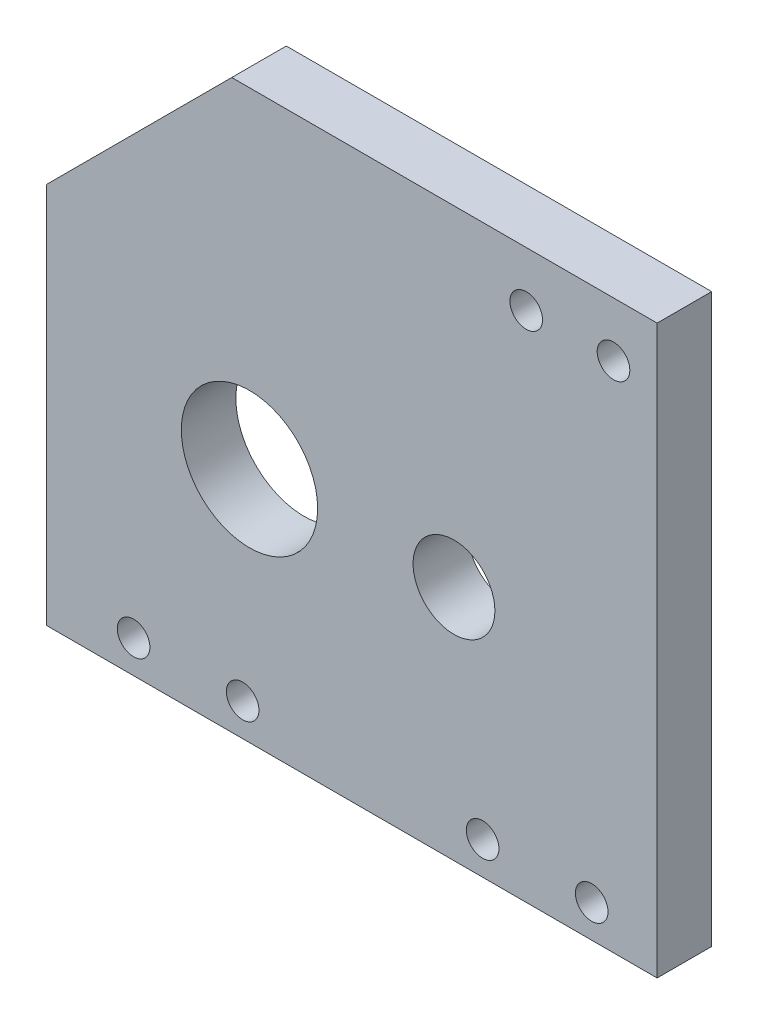
SolidWorks part; units mm, degrees
ref_plane "Front Plane" through (0, 0, 0) normal (0, 0, 1) x (1, 0, 0)
ref_plane "Top Plane" through (0, 0, 0) normal (0, 1, 0) x (1, 0, 0)
ref_plane "Right Plane" through (0, 0, 0) normal (1, 0, 0) x (0, 0, -1)
sketch "Sketch1" plane through (0, 0, 0) normal (0, 0, 1) x (1, 0, 0)
  line L1 (35.56, -33.02) -> (-35.56, -33.02)
  line L2 (35.56, -33.02) -> (35.56, 33.02)
  line L3 (35.56, 33.02) -> (-35.56, 33.02)
  line L4 (-35.56, -33.02) -> (-35.56, 33.02)
  line L5 (35.56, -33.02) -> (-35.56, 33.02) construction
  line L6 (35.56, 33.02) -> (-35.56, -33.02) construction
  circle A2 centre (-11.9062, -5.4381) radius 7.9375
  circle A3 centre (11.9062, -5.4381) radius 4.7625
  point P0 (0, 0)
  dimension "D11" = 15.875
  dimension "D12" = 9.525
  dimension "D1" = 71.12
  dimension "D2" = 66.04
  dimension "D9" = 5.4381
  dimension "D10" = 5.4381
  dimension "D13" = 11.9062
  dimension "D14" = 11.9062
extrude "Boss-Extrude1" add sketch "Sketch1" along normal blind 6.35
hole_wizard "#6 Clearance Hole1" positions "Sketch2" profile "Sketch3" hole size "#6" standard "ANSI Inch" end condition through all
sketch "Sketch2" plane through (0, 0, 6.35) normal (0, 0, 1) x (1, 0, 0)
  line L0 (-25.4, -29.21) -> (-12.7, -29.21)
  line L2 (15.24, -29.21) -> (27.94, -29.21)
  line L4 (-35.56, -33.02) -> (35.56, -33.02) construction
  line L5 (-35.56, 33.02) -> (-35.56, -33.02) construction
  point P0 (-25.4, -29.21)
  point P2 (-12.7, -29.21)
  point P4 (15.24, -29.21)
  point P6 (27.94, -29.21)
  dimension "D1" = 12.7
  dimension "D2" = 12.7
  dimension "D3" = 3.81
  dimension "D4" = 3.81
  dimension "D5" = 10.16
  dimension "D6" = 27.94
sketch "Sketch3" plane through (-25.4, -29.21, 6.35) normal (1, 0, 0) x (0, -1, 0)
  line L0 (0, 0) -> (0, 6.35)
  line L1 (0, 6.35) -> (1.8986, 6.35)
  line L2 (1.8986, 6.35) -> (1.8986, 0)
  line L5 (1.8986, 0) -> (0, 0)
  line L11 (0, -6.35) -> (0, 107.95) construction
  dimension "Thru Hole Dia." = 3.7973
  dimension "Thru Hole Depth" = 6.35
sketch "Sketch4" plane through (0, 0, 6.35) normal (0, 0, 1) x (1, 0, 0)
  line L0 (-35.56, 11.43) -> (-35.56, 33.02)
  line L1 (-35.56, 33.02) -> (-35.56, -33.02) construction
  line L2 (-35.56, 33.02) -> (-13.97, 33.02)
  line L3 (35.56, 33.02) -> (-35.56, 33.02) construction
  line L4 (-13.97, 33.02) -> (-35.56, 11.43)
  dimension "D1" = 21.59
  dimension "D2" = 21.59
extrude "Cut-Extrude1" cut sketch "Sketch4" against normal through all
hole_wizard "#6 Clearance Hole2" positions "Sketch5" profile "Sketch6" hole size "#6" standard "ANSI Inch" end condition through all
sketch "Sketch5" plane through (0, 0, 6.35) normal (0, 0, 1) x (1, 0, 0)
  line L0 (20.32, 26.67) -> (30.48, 26.67)
  line L2 (35.56, 33.02) -> (-13.97, 33.02) construction
  line L3 (35.56, -33.02) -> (35.56, 33.02) construction
  point P0 (20.32, 26.67)
  point P2 (30.48, 26.67)
  dimension "D1" = 6.35
  dimension "D2" = 10.16
  dimension "D3" = 5.08
sketch "Sketch6" plane through (20.32, 26.67, 6.35) normal (1, 0, 0) x (0, -1, 0)
  line L0 (0, 0) -> (0, 6.35)
  line L1 (0, 6.35) -> (1.8986, 6.35)
  line L2 (1.8986, 6.35) -> (1.8986, 0)
  line L5 (1.8986, 0) -> (0, 0)
  line L11 (0, -6.35) -> (0, 107.95) construction
  dimension "Thru Hole Dia." = 3.7973
  dimension "Thru Hole Depth" = 6.35
